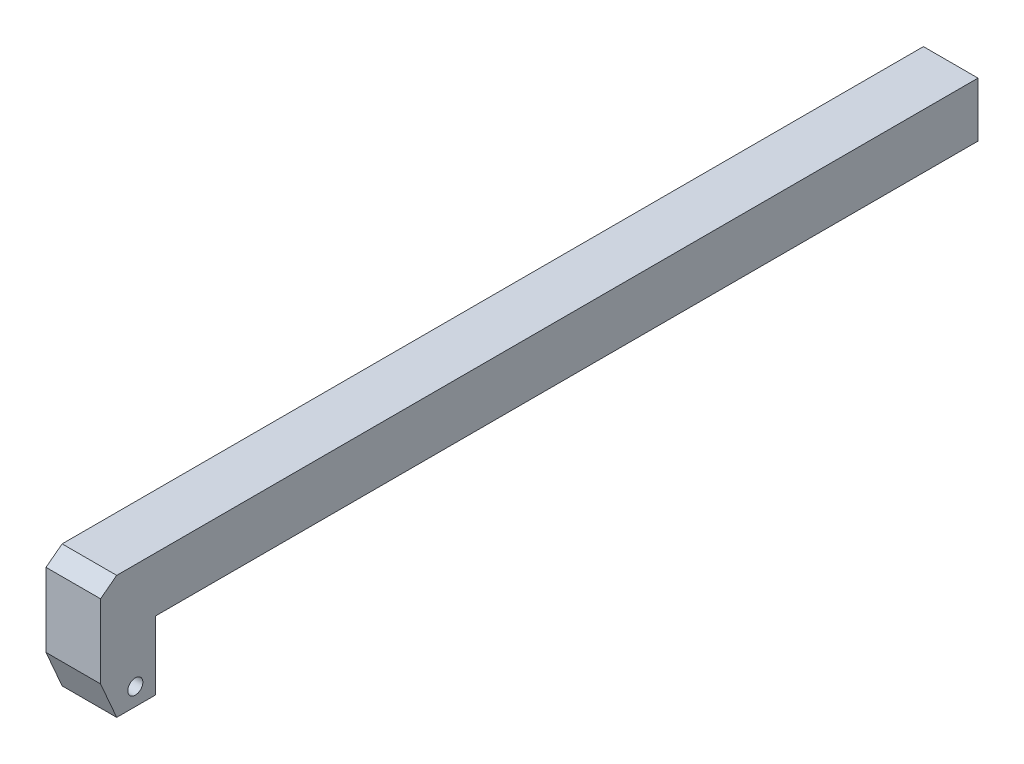
SolidWorks part; units mm, degrees
ref_plane "Front Plane" through (0, 0, 0) normal (0, 0, 1) x (1, 0, 0)
ref_plane "Top Plane" through (0, 0, 0) normal (0, 1, 0) x (1, 0, 0)
ref_plane "Right Plane" through (0, 0, 0) normal (1, 0, 0) x (0, 0, -1)
sketch "Sketch2" plane through (0, 0, 0) normal (0, 0, 1) x (1, 0, 0)
  line L1 (0, 0) -> (736.6, 0)
  line L2 (0, 0) -> (0, 736.6)
  line L3 (0, 736.6) -> (736.6, 736.6)
  line L4 (736.6, 0) -> (736.6, 736.6)
  dimension "D1" = 736.6
  dimension "D2" = 736.6
extrude "Boss-Extrude1" add sketch "Sketch2" along normal blind 11099.8
sketch "Sketch3" plane through (736.6, 0, 0) normal (1, 0, 0) x (0, 0, -1)
  line L0 (-11099.8, 736.6) -> (-11625.8192, 736.6)
  line L2 (-11625.8192, -923.8776) -> (-11099.8, -923.8776)
  line L3 (-11099.8, -923.8776) -> (-11099.8, 0)
  line L4 (-11099.8, 0) -> (0, 0) construction
  line L6 (-11099.8, 0) -> (-11099.8, 736.6)
  line L7 (-11625.8192, 736.6) -> (-11843.547, 571.2707)
  line L8 (-11843.547, 571.2707) -> (-11843.547, -423.5987)
  line L10 (-11843.547, -423.5987) -> (-11625.8192, -923.8776)
  circle A0 centre (-11374.5337, -687.7976) radius 101.6
  point P4 (-11374.5337, -687.7976)
  point P9 (-11625.8192, 736.6)
  point P13 (-11843.547, 571.2707)
extrude "Boss-Extrude2" add sketch "Sketch3" against normal blind 736.6 contours A0 | L6 L0 L7 L8 L10 L2 L3
